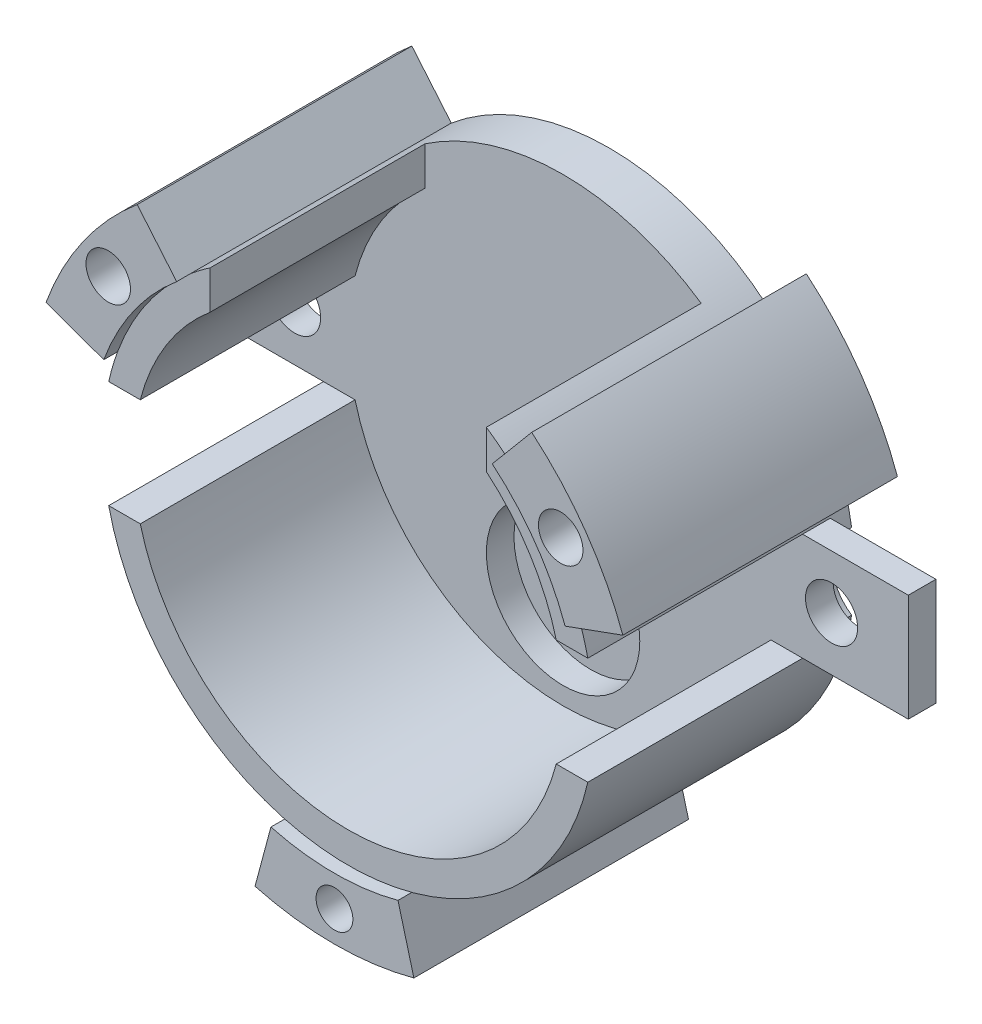
SolidWorks part; units mm, degrees
ref_plane "Piano frontale" through (0, 0, 0) normal (0, 0, 1) x (1, 0, 0)
ref_plane "Piano superiore" through (0, 0, 0) normal (0, 1, 0) x (1, 0, 0)
ref_plane "Piano destro" through (0, 0, 0) normal (1, 0, 0) x (0, 0, -1)
sketch "Schizzo1" plane through (0, 0, 0) normal (0, 0, 1) x (1, 0, 0)
  circle A0 centre (0, 0) radius 14
  circle A1 centre (0, 0) radius 16
  dimension "D1" = 28
  dimension "D2" = 32
extrude "Estrusione-Estrusione1" add sketch "Schizzo1" along normal blind 14
sketch "Schizzo2" plane through (0, 0, 0) normal (0, 0, -1) x (-1, 0, 0)
  circle A0 centre (0, 0) radius 16
extrude "Estrusione-Estrusione2" add sketch "Schizzo2" along normal blind 3
sketch "Schizzo3" plane through (0, 0, 0) normal (0, 0, 1) x (1, 0, 0)
  line L1 (16, -3.5) -> (-16, -3.5)
  line L2 (16, -3.5) -> (16, 3.5)
  line L3 (16, 3.5) -> (-16, 3.5)
  line L4 (-16, -3.5) -> (-16, 3.5)
  line L5 (16, -3.5) -> (-16, 3.5) construction
  line L6 (16, 3.5) -> (-16, -3.5) construction
  circle A0 centre (0, 0) radius 16 construction
  point P0 (0, 0)
  dimension "D1" = 7
extrude "Taglio-Estrusione1" cut sketch "Schizzo3" along normal up to surface (14 mm away) up to face at (16, 0, 14)
sketch "Schizzo4" plane through (0, 0, 0) normal (0, 0, 1) x (1, 0, 0)
  line L1 (22.5, 3.5) -> (-22.5, 3.5)
  line L2 (22.5, 3.5) -> (22.5, -3.5)
  line L3 (22.5, -3.5) -> (-22.5, -3.5)
  line L4 (-22.5, 3.5) -> (-22.5, -3.5)
  line L5 (22.5, 3.5) -> (-22.5, -3.5) construction
  line L6 (22.5, -3.5) -> (-22.5, 3.5) construction
  point P0 (0, 0)
  dimension "D1" = 7
  dimension "D2" = 45
extrude "Estrusione-Estrusione3" add sketch "Schizzo4" against normal blind 1.8
sketch "Schizzo6" plane through (0, 0, 0) normal (0, 0, 1) x (1, 0, 0)
  line L1 (-9, 16) -> (9, 16)
  line L2 (-9, 16) -> (-9, 0)
  line L3 (-9, 0) -> (9, 0)
  line L4 (9, 16) -> (9, 0)
  arc A0 (15.6125, 3.5) -> (-15.6125, 3.5) centre (0, 0) ccw construction
  point P4 (0, 0)
  dimension "D1" = 18
extrude "Taglio-Estrusione2" cut sketch "Schizzo6" along normal up to surface (14 mm away) up to face at (0, 9.25, 14)
sketch "Schizzo7" plane through (0, 0, 0) normal (0, 0, 1) x (1, 0, 0)
  line L0 (0, 0) -> (0, -7.85) construction
  circle A0 centre (0, -7.85) radius 5
  dimension "D2" = 10
  dimension "D1" = 7.85
extrude "Taglio-Estrusione3" cut sketch "Schizzo7" against normal up to surface (1.8 mm away) up to face at (-19.1531, 0, -1.8)
sketch "Schizzo8" plane through (0, 0, 0) normal (0, 0, 1) x (1, 0, 0)
  line L0 (0, 0) -> (17.5, 0) construction
  dimension "D1" = 17.5
hole_wizard "Foro per Vite M3-1" positions "Schizzo10" profile "Schizzo9" hole size "M3" standard "ISO"
sketch "Schizzo10" plane through (0, 0, 0) normal (0, 0, 1) x (1, 0, 0)
  point P0 (17.5, 0)
sketch "Schizzo9" plane through (17.5, 0, 0) normal (1, 0, 0) x (0, -1, 0)
  line L0 (0, 0) -> (0, 11.0215)
  line L1 (0, 11.0215) -> (1.7, 10)
  line L2 (1.7, 10) -> (1.7, 0)
  line L5 (1.7, 0) -> (0, 0)
  line L10 (0, 11.0215) -> (-1.7, 10) construction
  line L11 (0, -6.35) -> (0, 107.95) construction
  dimension "Hole Dia." = 3.4
  dimension "Hole Depth" = 10
  dimension "Drill Angle" = 118
mirror "Specchia1" about plane through (0, 0, 0) normal (1, 0, 0) of "Foro per Vite M3-1"
sketch "Schizzo11" plane through (0, 0, -3) normal (0, 0, -1) x (-1, 0, 0)
  line L0 (0, 0) -> (-16.383, 11.4715) construction
  line L1 (0, 0) -> (0, 11.0814) construction
  line L2 (-10.2846, 12.2567) -> (-12.8558, 15.3209)
  line L3 (-15.0351, 5.4723) -> (-18.7939, 6.8404)
  arc A0 (-12.8558, 15.3209) -> (-18.7939, 6.8404) centre (0, 0) ccw
  arc A1 (-10.2846, 12.2567) -> (-15.0351, 5.4723) centre (0, 0) ccw
  dimension "D2" = 40
  dimension "D6" = 16
  dimension "D1" = 55
  dimension "D3" = 15
  dimension "D4" = 15
  dimension "D5" = 4
extrude "Estrusione-Estrusione4" add sketch "Schizzo11" against normal blind 17.9
mirror "Specchia2" about plane through (0, 0, 0) normal (1, 0, 0) of "Estrusione-Estrusione4"
sketch "Schizzo13" plane through (0, 0, -3) normal (0, 0, -1) x (-1, 0, 0)
  line L0 (0, 0) -> (0, -20) construction
  line L1 (-4.1411, -15.4548) -> (-5.1764, -19.3185)
  line L2 (4.1411, -15.4548) -> (5.1764, -19.3185)
  arc A0 (-4.1411, -15.4548) -> (4.1411, -15.4548) centre (0, 0) ccw
  arc A1 (-5.1764, -19.3185) -> (5.1764, -19.3185) centre (0, 0) ccw
  dimension "D3" = 32
  dimension "D4" = 40
  dimension "D1" = 15
  dimension "D2" = 15
  dimension "D5" = 4
extrude "Estrusione-Estrusione6" add sketch "Schizzo13" against normal blind 17.9 separate body
sketch "Schizzo14" plane through (0, 0, 14.9) normal (0, 0, 1) x (1, 0, 0)
  line L0 (-16.383, 11.4715) -> (-14.7447, 10.3244) construction
  arc A0 (-12.8558, 15.3209) -> (-18.7939, 6.8404) centre (0, 0) ccw construction
  dimension "D1" = 2
hole_wizard "Foro per Vite M2.5-1" positions "Schizzo17" profile "Schizzo16" hole size "M2.5" standard "ISO"
sketch "Schizzo17" plane through (0, 0, 14.9) normal (0, 0, 1) x (1, 0, 0)
  point P0 (-14.7447, 10.3244)
sketch "Schizzo16" plane through (-14.7447, 10.3244, 14.9) normal (1, 0, 0) x (0, -1, 0)
  line L0 (0, 0) -> (0, 10.8712)
  line L1 (0, 10.8712) -> (1.45, 10)
  line L2 (1.45, 10) -> (1.45, 0)
  line L5 (1.45, 0) -> (0, 0)
  line L10 (0, 10.8712) -> (-1.45, 10) construction
  line L11 (0, -6.35) -> (0, 107.95) construction
  dimension "Hole Dia." = 2.9
  dimension "Hole Depth" = 10
  dimension "Drill Angle" = 118
mirror "Specchia3" about plane through (0, 0, 0) normal (1, 0, 0) of "Foro per Vite M2.5-1"
sketch "Schizzo18" plane through (0, 0, 14.9) normal (0, 0, 1) x (1, 0, 0)
  line L0 (0, -20) -> (0, -18) construction
  arc A0 (-5.1764, -19.3185) -> (5.1764, -19.3185) centre (0, 0) ccw construction
  dimension "D1" = 2
hole_wizard "Foro per Vite M2-1" positions "Schizzo19" profile "Schizzo20" hole size "M2" standard "ISO"
sketch "Schizzo19" plane through (0, 0, 14.9) normal (0, 0, 1) x (1, 0, 0)
  point P0 (0, -18)
sketch "Schizzo20" plane through (0, -18, 14.9) normal (1, 0, 0) x (0, -1, 0)
  line L0 (0, 0) -> (0, 10.721)
  line L1 (0, 10.721) -> (1.2, 10)
  line L2 (1.2, 10) -> (1.2, 0)
  line L5 (1.2, 0) -> (0, 0)
  line L10 (0, 10.721) -> (-1.2, 10) construction
  line L11 (0, -6.35) -> (0, 107.95) construction
  dimension "Hole Dia." = 2.4
  dimension "Hole Depth" = 10
  dimension "Drill Angle" = 118
sketch "Schizzo21" plane through (0, 0, -1.8) normal (0, 0, -1) x (-1, 0, 0)
  circle A0 centre (-17.5, 0) radius 3
  circle A1 centre (17.5, 0) radius 3
  dimension "D1" = 6
  dimension "D2" = 6
extrude "Taglio-Estrusione4" cut sketch "Schizzo21" along normal blind 10
